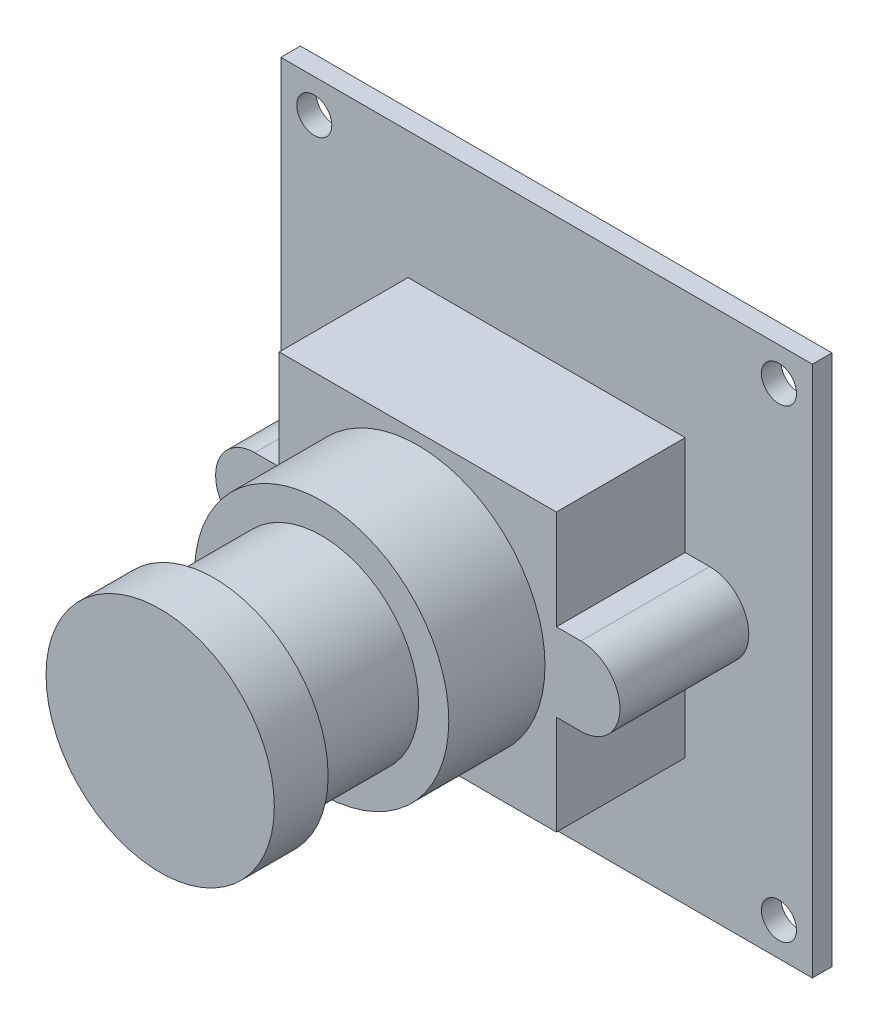
SolidWorks part; units mm, degrees
ref_plane "Front" through (0, 0, 0) normal (0, 0, 1) x (1, 0, 0)
ref_plane "Top" through (0, 0, 0) normal (0, 1, 0) x (1, 0, 0)
ref_plane "Right" through (0, 0, 0) normal (1, 0, 0) x (0, 0, -1)
sketch "Sketch1" plane through (0, 0, 0) normal (0, 0, 1) x (1, 0, 0)
  line L1 (-16.3, 16.3) -> (16.3, 16.3)
  line L2 (-16.3, 16.3) -> (-16.3, -16.3)
  line L3 (-16.3, -16.3) -> (16.3, -16.3)
  line L4 (16.3, 16.3) -> (16.3, -16.3)
  line L5 (-16.3, 16.3) -> (16.3, -16.3) construction
  line L6 (-16.3, -16.3) -> (16.3, 16.3) construction
  point P0 (0, 0)
  dimension "D1" = 32.6
extrude "Boss-Extrude1" add sketch "Sketch1" along normal blind 1.2
sketch "Sketch2" plane through (0, 0, 1.2) normal (0, 0, 1) x (1, 0, 0)
  line L1 (-14.25, 14.25) -> (14.25, 14.25)
  line L2 (-14.25, 14.25) -> (-14.25, -14.25)
  line L3 (-14.25, -14.25) -> (14.25, -14.25)
  line L4 (14.25, 14.25) -> (14.25, -14.25)
  line L5 (-14.25, 14.25) -> (14.25, -14.25) construction
  line L6 (-14.25, -14.25) -> (14.25, 14.25) construction
  point P0 (0, 0)
  dimension "D1" = 28.5
sketch "Sketch3" plane through (0, 0, 1.2) normal (0, 0, 1) x (1, 0, 0)
  circle A0 centre (-14.25, 14.25) radius 1.075
  circle A1 centre (14.25, 14.25) radius 1.075
  circle A2 centre (14.25, -14.25) radius 1.075
  circle A3 centre (-14.25, -14.25) radius 1.075
  dimension "D1" = 2.15
extrude "Cut-Extrude1" cut sketch "Sketch3" against normal through all
sketch "Sketch4" plane through (0, 0, 1.2) normal (0, 0, 1) x (1, 0, 0)
  line L1 (-8.5, 8.5) -> (8.5, 8.5)
  line L2 (-8.5, 8.5) -> (-8.5, -8.5)
  line L3 (-8.5, -8.5) -> (8.5, -8.5)
  line L4 (8.5, 8.5) -> (8.5, -8.5)
  line L5 (-8.5, 8.5) -> (8.5, -8.5) construction
  line L6 (-8.5, -8.5) -> (8.5, 8.5) construction
  point P0 (0, 0)
  dimension "D1" = 17
extrude "Boss-Extrude2" add sketch "Sketch4" along normal blind 7.9
sketch "Sketch5" plane through (0, 0, 1.2) normal (0, 0, 1) x (1, 0, 0)
  line L0 (-10, 0) -> (10, 0) construction
  line L1 (-14.25, 14.25) -> (14.25, -14.25) construction
  line L2 (-10, 2.4) -> (10, 2.4)
  line L3 (-10, -2.4) -> (10, -2.4)
  arc A0 (-10, 2.4) -> (-10, -2.4) centre (-10, 0) ccw
  arc A1 (10, -2.4) -> (10, 2.4) centre (10, 0) ccw
  point P4 (0, 0)
  dimension "D2" = 20
  dimension "D1" = 4.8
extrude "Boss-Extrude3" add sketch "Sketch5" along normal up to surface (7.9 mm away) up to face at (0, 0, 9.1)
sketch "Sketch6" plane through (0, 0, 9.1) normal (0, 0, 1) x (1, 0, 0)
  circle A0 centre (0, 0) radius 7.8
  dimension "D1" = 15.6
extrude "Boss-Extrude4" add sketch "Sketch6" along normal blind 5.9
sketch "Sketch7" plane through (0, 0, 15) normal (0, 0, 1) x (1, 0, 0)
  circle A0 centre (0, 0) radius 5.95
  dimension "D1" = 11.9
extrude "Boss-Extrude5" add sketch "Sketch7" along normal blind 6.6
sketch "Sketch8" plane through (0, 0, 21.6) normal (0, 0, 1) x (1, 0, 0)
  circle A0 centre (0, 0) radius 7
  dimension "D1" = 14
extrude "Boss-Extrude6" add sketch "Sketch8" along normal blind 3.3
equation "\"D2@Sketch5\"=24.8 - \"D1@Sketch5\""
